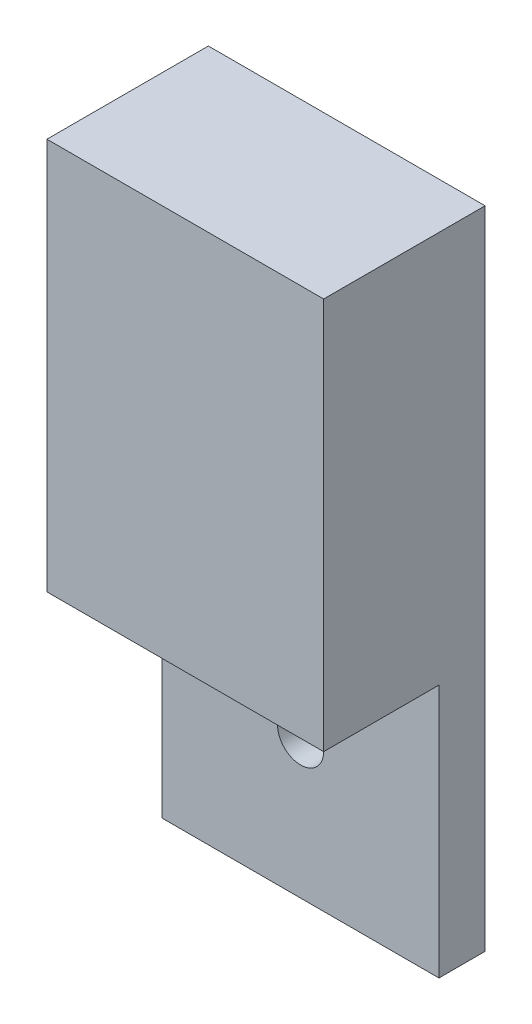
SolidWorks part; units mm, degrees
ref_plane "前视基准面" through (0, 0, 0) normal (0, 0, 1) x (1, 0, 0)
ref_plane "上视基准面" through (0, 0, 0) normal (0, 1, 0) x (1, 0, 0)
ref_plane "右视基准面" through (0, 0, 0) normal (1, 0, 0) x (0, 0, -1)
sketch "草图1" plane through (0, 0, 0) normal (0, 0, 1) x (1, 0, 0)
  line L1 (-6, -14) -> (6, -14)
  line L2 (-6, -14) -> (-6, 14)
  line L3 (-6, 14) -> (6, 14)
  line L4 (6, -14) -> (6, 14)
  line L5 (-6, -14) -> (6, 14) construction
  line L6 (-6, 14) -> (6, -14) construction
  point P0 (0, 0)
  dimension "D1" = 28
  dimension "D2" = 12
sketch "草图2" plane through (0, 0, 0) normal (0, 0, 1) x (1, 0, 0)
  line L0 (6, -14) -> (6, 14) construction
  line L1 (-6, 14) -> (6, 14)
  line L2 (-6, 14) -> (-6, -3)
  line L3 (-6, -3) -> (6, -3)
  line L4 (6, 14) -> (6, -3)
  dimension "D1" = 17
extrude "凸台-拉伸1" add sketch "草图1" against normal blind 2
extrude "凸台-拉伸2" add sketch "草图2" along normal blind 5
sketch "草图3" plane through (0, 0, 0) normal (0, 0, 1) x (1, 0, 0)
  line L0 (0, 0) -> (0, -8) construction
  circle A0 centre (0, -8) radius 1
  dimension "D1" = 8
extrude "切除-拉伸1" cut sketch "草图3" against normal up to next
